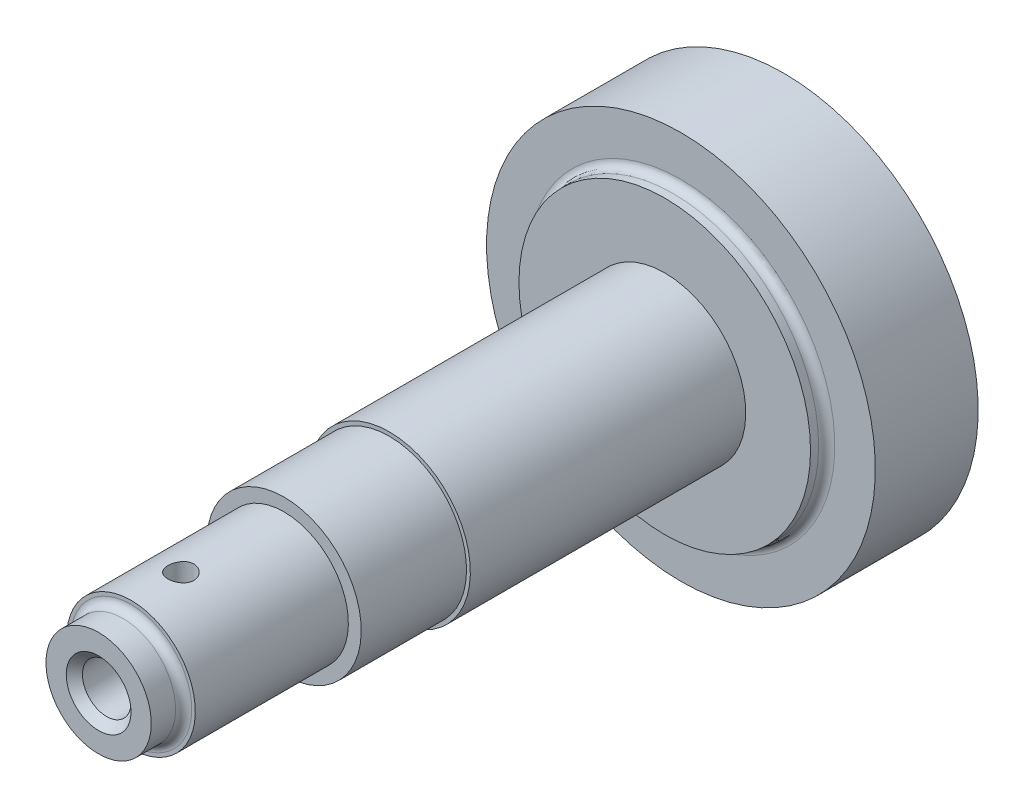
SolidWorks part; units mm, degrees
material "Alloy Steel (SS)"
ref_plane "Front Plane" through (0, 0, 0) normal (0, 0, 1) x (1, 0, 0)
ref_plane "Top Plane" through (0, 0, 0) normal (0, 1, 0) x (1, 0, 0)
ref_plane "Right Plane" through (0, 0, 0) normal (1, 0, 0) x (0, 0, -1)
sketch "Sketch1" plane through (0, 0, 0) normal (1, 0, 0) x (0, 0, -1)
  line L0 (0, 0) -> (-23.949, 0)
  line L1 (-23.949, 0) -> (-23.949, 1.5)
  line L2 (-23.949, 1.5) -> (-34.949, 1.5)
  line L3 (-34.949, 1.5) -> (-34.949, 3.25)
  line L4 (-17, 5) -> (0, 5)
  line L5 (1, 9) -> (1, 12)
  line L6 (1, 12) -> (7.35, 12)
  line L7 (7.35, 12) -> (7.35, 0)
  line L8 (7.35, 0) -> (0, 0)
  line L9 (1, 9) -> (0, 9)
  line L10 (0, 9) -> (0, 5)
  line L11 (-17, 5) -> (-17, 4.7625)
  line L12 (-17, 4.7625) -> (-23.5, 4.7625)
  line L13 (-23.5, 4.7625) -> (-23.5, 3.9687)
  line L14 (-23.5, 3.9687) -> (-32.949, 3.9687)
  line L15 (-32.949, 3.9687) -> (-32.949, 3.75)
  line L16 (-33.449, 3.25) -> (-34.949, 3.25)
  arc A0 (-32.949, 3.75) -> (-33.449, 3.25) centre (-33.449, 3.75) cw
  dimension "D15" = 0.5
  dimension "D1" = 1.5
  dimension "D2" = 5
  dimension "D3" = 12
  dimension "D4" = 6.35
  dimension "D5" = 17
  dimension "D6" = 1
  dimension "D7" = 9
  dimension "D8" = 11
  dimension "D9" = 6.5
  dimension "D10" = 4.7625
  dimension "D11" = 17.949
  dimension "D12" = 3.9688
  dimension "D13" = 2
  dimension "D14" = 3.25
revolve "Revolve1" add sketch "Sketch1" angle 360 about L8
cosmetic thread "Cosmetic Thread1"
hole_wizard "M2 Tapped Hole1" positions "Sketch3" profile "Sketch4" tap size "M2" standard "DIN"
sketch "Sketch3" plane through (0, 0, 0) normal (0, 1, 0) x (1, 0, 0)
  point P2 (0, -29.869)
  dimension "D1" = 29.869
sketch "Sketch4" plane through (0, 0, 29.869) normal (1, 0, 0) x (0, 0, -1)
  line L0 (0, 0) -> (0, 12)
  line L1 (0, 12) -> (0.8, 12)
  line L2 (0.8, 12) -> (0.8, 0)
  line L5 (0.8, 0) -> (0, 0)
  line L11 (0, -6.35) -> (0, 107.95) construction
  dimension "Thru Tap Drill Dia." = 1.6
  dimension "Thru Tap Drill Depth" = 12
cosmetic thread "Hole Thread1" parameters "D2"=2
hole_wizard "M2.5 Tapped Hole1" positions "Sketch6" profile "Sketch5" tap size "M2.5" standard "DIN"
sketch "Sketch6" plane through (0, 0, -7.35) normal (0, 0, 1) x (1, 0, 0)
  point P0 (0, 8)
  point P6 (6.9282, 4)
  point P7 (6.9282, -4)
  point P8 (0, -8)
  point P9 (-6.9282, -4)
  point P10 (-6.9282, 4)
  dimension "D2" = 8
  dimension "D3" = 8
  dimension "D1" = 6
cosmetic thread "Hole Thread3"
cosmetic thread "Hole Thread4"
cosmetic thread "Hole Thread5"
cosmetic thread "Hole Thread6"
cosmetic thread "Hole Thread7"
cosmetic thread "Hole Thread8"
sketch "Sketch5" plane through (0, 8, -7.35) normal (1, 0, 0) x (0, 1, 0)
  line L0 (0, 0) -> (0, 5.9659)
  line L1 (0, 5.9659) -> (1.025, 5.35)
  line L2 (1.025, 5.35) -> (1.025, 0)
  line L5 (1.025, 0) -> (0, 0)
  line L10 (0, 5.9659) -> (-1.025, 5.35) construction
  line L11 (0, -6.35) -> (0, 107.95) construction
  dimension "Tap Drill Dia." = 2.05
  dimension "Tap Drill Depth" = 5.35
  dimension "Drill Angle" = 118
fillet "Fillet1" radius 0.5 1 edges at (0, 9, -1)
chamfer "Chamfer1" distance 0.5 angle 45 1 edges at (0, 1.5, 34.949)
